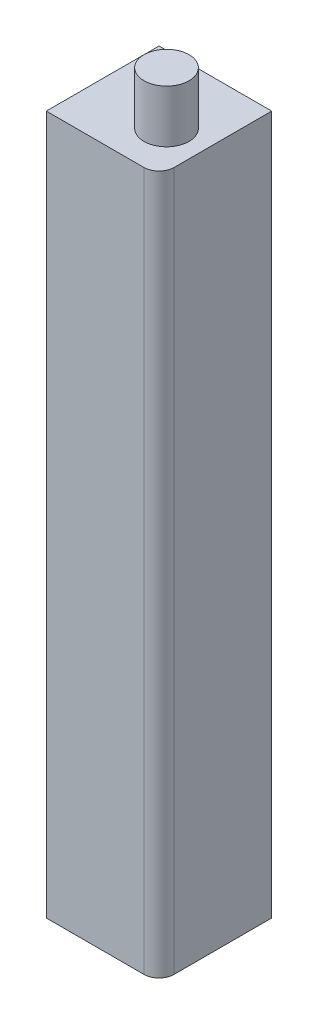
SolidWorks part; units mm, degrees
ref_plane "Front Plane" through (0, 0, 0) normal (0, 0, 1) x (1, 0, 0)
ref_plane "Top Plane" through (0, 0, 0) normal (0, 1, 0) x (1, 0, 0)
ref_plane "Right Plane" through (0, 0, 0) normal (1, 0, 0) x (0, 0, -1)
sketch "Sketch1" plane through (0, 0, 0) normal (0, 1, 0) x (1, 0, 0)
  line L0 (-68.486, 0) -> (57.6746, 0) construction
  line L1 (0, 62.7099) -> (0, -58.019) construction
  line L3 (-7.5, -7.5) -> (7.5, -7.5)
  line L4 (-7.5, -7.5) -> (-7.5, 7.5)
  line L5 (-7.5, 7.5) -> (7.5, 7.5)
  line L6 (7.5, -7.5) -> (7.5, 7.5)
  line L7 (-7.5, -7.5) -> (7.5, 7.5) construction
  line L8 (-7.5, 7.5) -> (7.5, -7.5) construction
  point P5 (0, 0)
  dimension "D1" = 15
  dimension "D2" = 15
extrude "Boss-Extrude1" add sketch "Sketch1" along normal blind 93
sketch "Sketch2" plane through (0, 93, 0) normal (0, 1, 0) x (1, 0, 0)
  line L0 (7.5, -7.5) -> (7.5, 7.5) construction
  line L1 (-7.5, -7.5) -> (7.5, -7.5) construction
  circle A0 centre (2.5, -1.5) radius 3
  dimension "D1" = 6
  dimension "D2" = 5
  dimension "D3" = 6
extrude "Boss-Extrude2" add sketch "Sketch2" along normal blind 7
fillet "Fillet1" radius 2 1 edges at (7.5, 46.5, 7.5)
